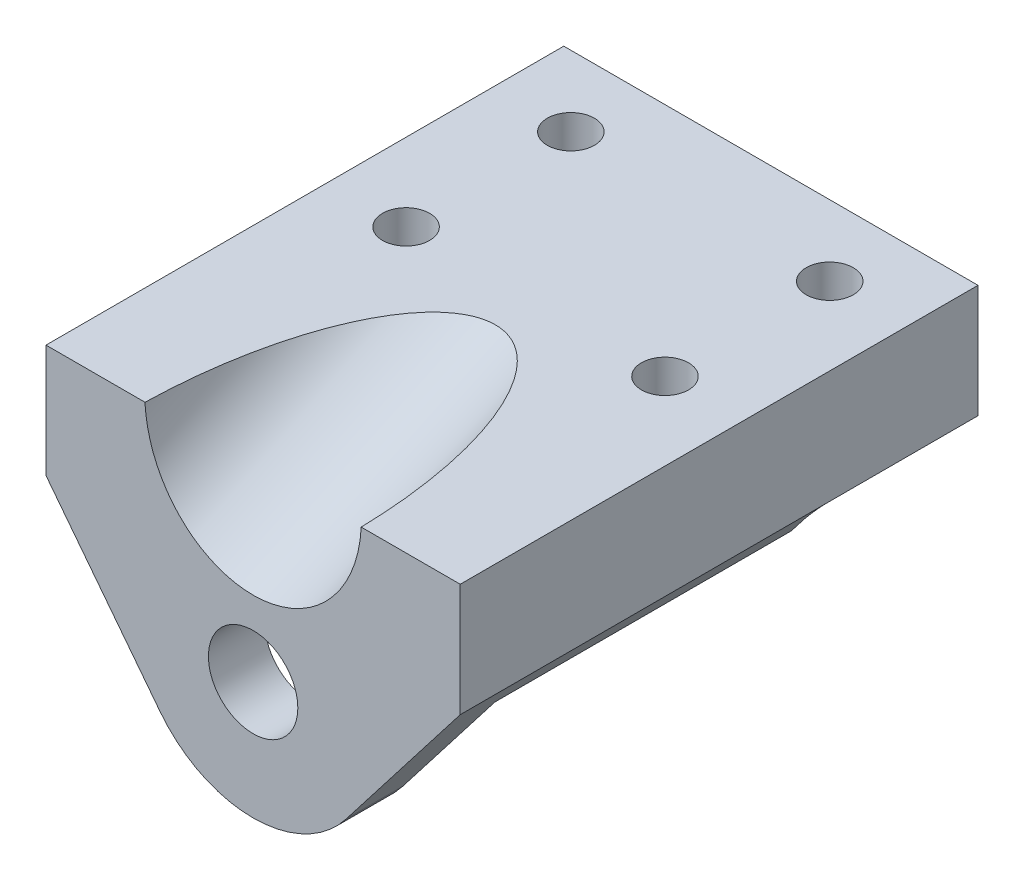
SolidWorks part; units mm, degrees
ref_plane "Front Plane" through (0, 0, 0) normal (0, 0, 1) x (1, 0, 0)
ref_plane "Top Plane" through (0, 0, 0) normal (0, 1, 0) x (1, 0, 0)
ref_plane "Right Plane" through (0, 0, 0) normal (1, 0, 0) x (0, 0, -1)
sketch "Sketch1" plane through (0, 0, 0) normal (1, 0, 0) x (0, 0, -1)
  line L0 (0, 0) -> (0, -65)
  line L1 (0, -65) -> (12, -65)
  line L2 (12, -65) -> (12, -30)
  line L3 (12, -30) -> (75, -30)
  line L4 (75, -30) -> (75, -27)
  line L5 (78, -24) -> (110, -24)
  line L6 (110, -24) -> (110, 0)
  line L7 (110, 0) -> (0, 0)
  line L8 (0, -24) -> (68.9524, 8.153) construction
  line L9 (12.3433, 10.2481) -> (31.1113, -30) construction
  arc A0 (75, -27) -> (78, -24) centre (78, -27) cw
  point P11 (75, -24)
  point P14 (31.1113, -30)
  dimension "D7" = 3
  dimension "D1" = 6
  dimension "D2" = 65
  dimension "D3" = 12
  dimension "D4" = 35
  dimension "D5" = 24
  dimension "D6" = 110
  dimension "D8" = 25
  dimension "D9" = 24
extrude "Boss-Extrude1" add sketch "Sketch1" along normal mid plane 88
ref_plane "Plane3" through (0, 6.5581, -14.064) normal (0, -0.4226, 0.9063) x (1, 0, 0)
sketch "Sketch5" plane through (0, 6.5581, -14.064) normal (0, -0.4226, 0.9063) x (1, 0, 0)
  line L0 (0, 4.0715) -> (0, -40.3375) construction
  circle A0 centre (0, 1.2486) radius 23
  point P2 (0, 0)
  point P3 (0, 0)
  dimension "D1" = 46
extrude "Cut-Extrude1" cut sketch "Sketch5" against normal up to next and the other way up to next
sketch "Sketch6" plane through (0, 0, 0) normal (0, 1, 0) x (1, 0, 0)
  line L0 (44, 110) -> (-44, 110) construction
  line L1 (0, -5.3661) -> (0, 10.5486) construction
  line L2 (0, 0) -> (0, 68.9524) construction
  circle A0 centre (27.5, 95) radius 5
  circle A1 centre (-27.5, 95) radius 5
  circle A2 centre (-27.5, 60) radius 5
  circle A3 centre (27.5, 60) radius 5
  point P8 (0, 0)
  point P9 (0, 0)
  dimension "D1" = 10
  dimension "D2" = 15
  dimension "D3" = 27.5
  dimension "D6" = 35
  dimension "D7" = 55
  dimension "D4" = 2
  dimension "D5" = 2
extrude "Cut-Extrude2" cut sketch "Sketch6" against normal up to next
sketch "Sketch7" plane through (0, 0, 0) normal (0, 0, 1) x (1, 0, 0)
  line L0 (44, -24) -> (19.7692, -55.3029)
  line L1 (44, 0) -> (44, -65) construction
  line L2 (0, -65) -> (0, -30) construction
  line L3 (44, -65) -> (-44, -65) construction
  line L4 (0, 4.8515) -> (0, -3.4998) construction
  line L5 (0, -24) -> (0, 8.153) construction
  line L6 (-44, -24) -> (-19.7692, -55.3029)
  arc A0 (-19.7692, -55.3029) -> (19.7692, -55.3029) centre (0, -40) ccw
  circle A1 centre (0, -40) radius 9.5
  line M7 (-44, 0) -> (-44, -65)
  line M8 (-44, -65) -> (44, -65)
  line M9 (44, -65) -> (44, 0)
  dimension "D1" = 24
  dimension "D3" = 19
  dimension "D2" = 40
extrude "Cut-Extrude3" cut sketch "Sketch7" against normal up to next contours A0 L0 M8 M9 | A1 | A0 L6 M7 M8
